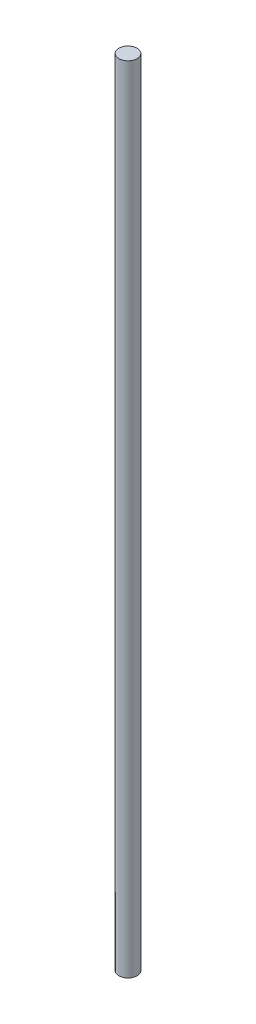
SolidWorks part; units mm, degrees
ref_plane "Front Plane" through (0, 0, 0) normal (0, 0, 1) x (1, 0, 0)
ref_plane "Top Plane" through (0, 0, 0) normal (0, 1, 0) x (1, 0, 0)
ref_plane "Right Plane" through (0, 0, 0) normal (1, 0, 0) x (0, 0, -1)
sketch "Sketch1" plane through (0, 0, 0) normal (0, 1, 0) x (1, 0, 0)
  circle A0 centre (0, 0) radius 4
  dimension "D1" = 8
extrude "Boss-Extrude1" add sketch "Sketch1" along normal blind 350
equation "\"Y-ROD-SPACING\"=75"
equation "\"Y-BED-OFFSET\"=2"
equation "\"Y-BED-ROD-INSET\"=3.5"
equation "\"T-SLOT-NUT-FILLET-RADIUS\"=0.25"
equation "\"T-SLOT-SCREW-SHAFT-RADIUS\"=1.75"
equation "\"T-SLOT-SCREW-SHAFT-CUTOUT-LENGTH\"=10.5"
equation "\"T-SLOT-NUT-DEPTH\"=4.2"
equation "\"T-SLOT-NUT-WIDTH\"=3"
equation "\"T-SLOT-NUT-END-DISTANCE\"=8"
equation "\"ACRYLIC-THICKNESS\"=10"
equation "\"ACRYLIC-TAB-CUTOUT-SIZE\"=\"ACRYLIC-THICKNESS\"+\"ACRYLIC-TAB-TOLERANCE\"*2"
equation "\"ACRYLIC-TAB-WIDTH\"=\"ACRYLIC-THICKNESS\""
equation "\"ACRYLIC-M3-HOLE\"=3.2"
equation "\"SMOOTHROD-CAP-SCREW-DISTANCE\"=20"
equation "\"FRAME-WIDTH-INNER\"=370"
equation "\"NEMA17-HOLE-SPACING\"=31"
equation "\"NEMA17-CENTRAL-CUTOUT\"=22.5"
equation "\"Z-BRACKET-REACH\"=55"
equation "\"TOP-BRACKET-SPACING\"=40"
equation "\"SMOOTHROD-X-LENGTH\"=350"
equation "\"SMOOTHROD-Y-LENGTH\"=350"
equation "\"SMOOTHROD-Z-LENGTH\"=350"
equation "\"SMOOTHROD-TIGHTENING-HEADROOM\"=1"
equation "\"LEADSCREW-Z-LENGTH\"=300"
equation "\"D1@Boss-Extrude1\"=\"SMOOTHROD-X-LENGTH\""
